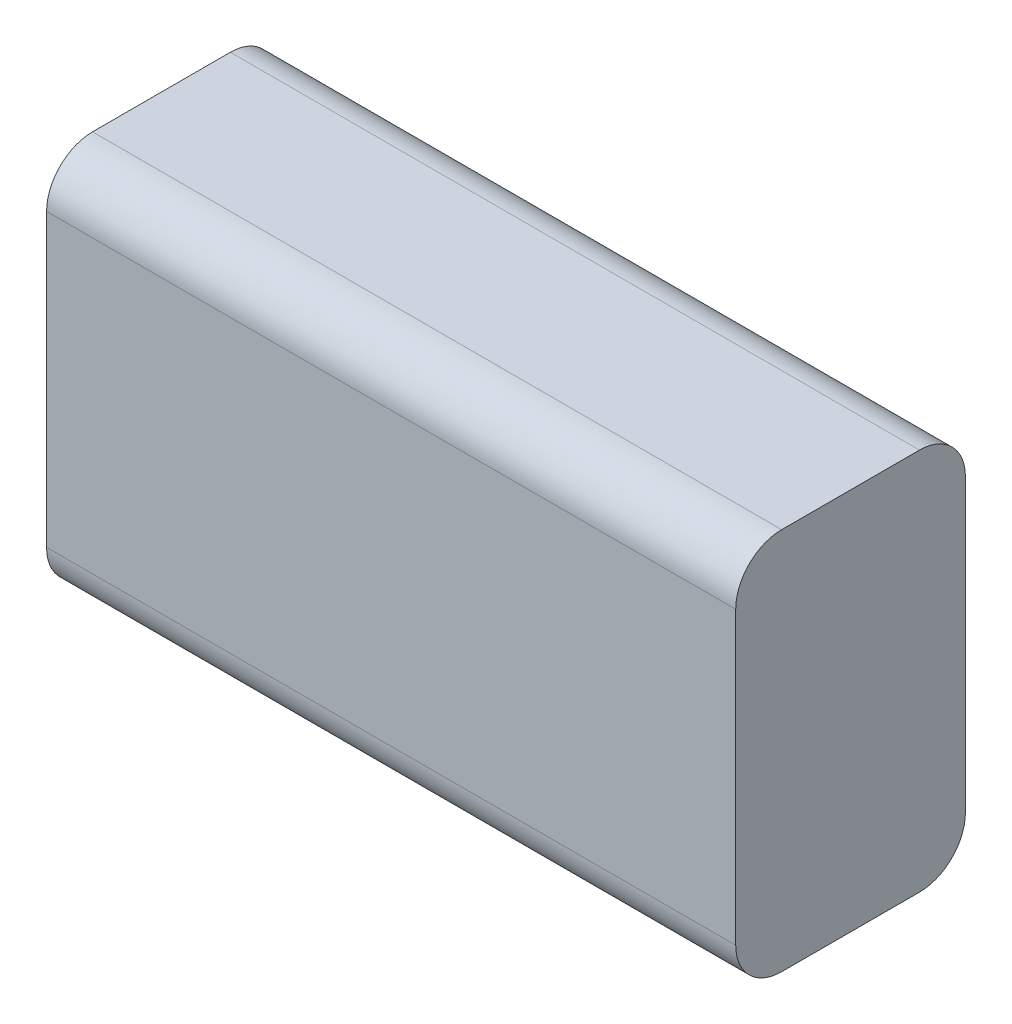
SolidWorks part; units mm, degrees
ref_plane "Plano frontal" through (0, 0, 0) normal (0, 0, 1) x (1, 0, 0)
ref_plane "Plano superior" through (0, 0, 0) normal (0, 1, 0) x (1, 0, 0)
ref_plane "Plano direito" through (0, 0, 0) normal (1, 0, 0) x (0, 0, -1)
sketch "Esboço1" plane through (0, 0, 0) normal (0, 0, 1) x (1, 0, 0)
  line L1 (0, 0) -> (45, 0)
  line L2 (0, 0) -> (0, 25)
  line L3 (0, 25) -> (45, 25)
  line L4 (45, 0) -> (45, 25)
  dimension "D1" = 25
  dimension "D2" = 45
extrude "Ressalto-extrusão1" add sketch "Esboço1" along normal blind 15
fillet "Filete1" radius 3 4 edges at (22.5, 0, 0) (22.5, 0, 15) (22.5, 25, 0) (22.5, 25, 15)
